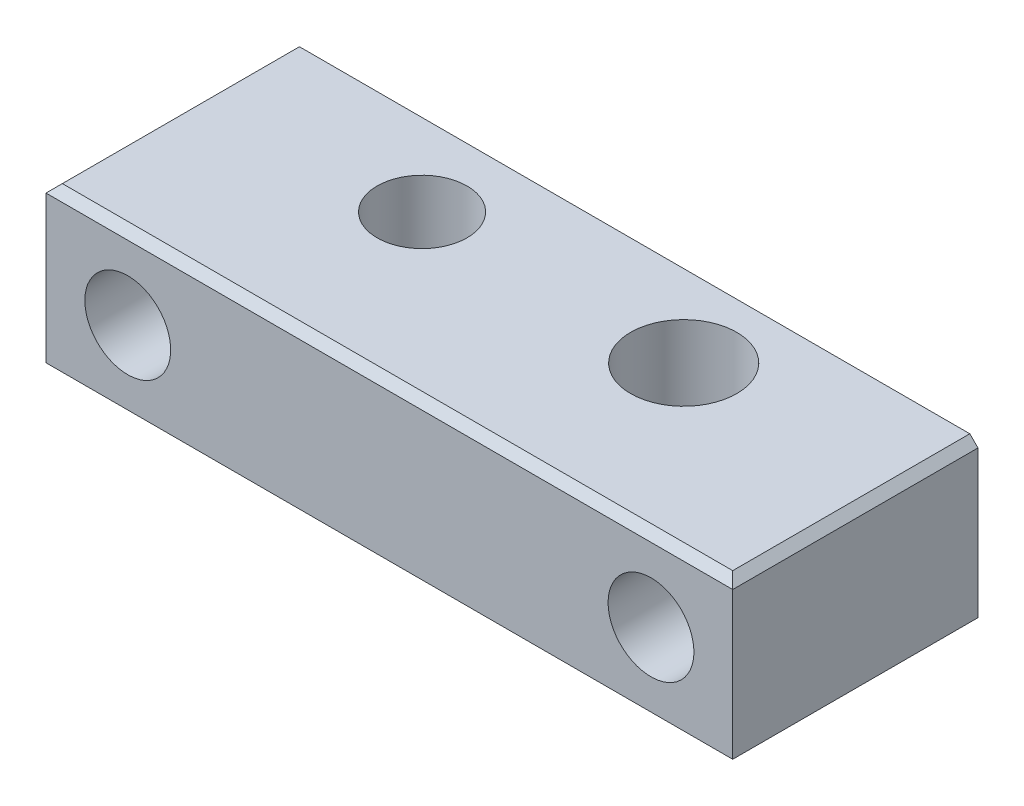
SolidWorks part; units mm, degrees
ref_plane "Front Plane" through (0, 0, 0) normal (0, 0, 1) x (1, 0, 0)
ref_plane "Top Plane" through (0, 0, 0) normal (0, 1, 0) x (1, 0, 0)
ref_plane "Right Plane" through (0, 0, 0) normal (1, 0, 0) x (0, 0, -1)
sketch "Sketch1" plane through (0, 0, 0) normal (0, 1, 0) x (1, 0, 0)
  line L1 (-66.675, -23.8125) -> (66.675, -23.8125)
  line L2 (-66.675, -23.8125) -> (-66.675, 23.8125)
  line L3 (-66.675, 23.8125) -> (66.675, 23.8125)
  line L4 (66.675, -23.8125) -> (66.675, 23.8125)
  line L5 (-66.675, -23.8125) -> (66.675, 23.8125) construction
  line L6 (-66.675, 23.8125) -> (66.675, -23.8125) construction
  point P0 (0, 0)
  dimension "D1" = 66.675
  dimension "D2" = 23.8125
extrude "Boss-Extrude1" add sketch "Sketch1" along normal mid plane 31.7246
sketch "Sketch2" plane through (0, 0, 0) normal (0, 0, 1) x (1, 0, 0)
  circle A0 centre (-50.8, -0.0127) radius 8.3312
  circle A1 centre (50.8, -0.0127) radius 8.3312
  point P4 (0, 0)
  dimension "D1" = 16.6624
  dimension "D2" = 16.6624
  dimension "D3" = 101.6
  dimension "D4" = 50.8
  dimension "D5" = 0.0127
extrude "Cut-Extrude2" cut sketch "Sketch2" along normal blind 133.35 from offset 23.8125
sketch "Sketch3" plane through (0, 0, 0) normal (0, 0, 1) x (1, 0, 0)
  circle A0 centre (-50.8, -0.0127) radius 12.7
  circle A1 centre (50.8, -0.0127) radius 12.7
  point P4 (0, 0)
  dimension "D1" = 25.4
  dimension "D2" = 25.4
  dimension "D3" = 101.6
  dimension "D4" = 50.8
  dimension "D5" = 0.0127
extrude "Cut-Extrude4" cut sketch "Sketch3" along normal blind 15.875 from offset 23.8125
sketch "Sketch4" plane through (0, 0, 0) normal (0, 1, 0) x (1, 0, 0)
  circle A0 centre (25.4, 7.9375) radius 10.3124
  point P2 (0, 0)
  dimension "D1" = 20.6248
  dimension "D2" = 25.4
  dimension "D3" = 7.9375
extrude "Cut-Extrude6" cut sketch "Sketch4" along normal through all from offset 15.8623
hole_wizard "3/4-16 Tapped Hole1" positions "Sketch6" profile "Sketch5" tap size "3/4-16" standard "ANSI Inch"
sketch "Sketch6" plane through (0, -15.8623, 0) normal (0, -1, 0) x (-1, 0, 0)
  line L0 (0, 0) -> (25.4, 7.9375) construction
  line L1 (-66.675, -23.8125) -> (-66.675, 23.8125) construction
  line L2 (66.675, -23.8125) -> (-66.675, -23.8125) construction
  point P0 (25.4, 7.9375)
  dimension "D1" = 92.075
  dimension "D2" = 31.75
sketch "Sketch5" plane through (-25.4, -15.8623, -7.9375) normal (1, 0, 0) x (0, 0, -1)
  line L0 (0, 0) -> (0, 36.9709)
  line L1 (0, 36.9709) -> (8.7312, 31.7246)
  line L2 (8.7312, 31.7246) -> (8.7312, 0)
  line L5 (8.7312, 0) -> (0, 0)
  line L10 (0, 36.9709) -> (-8.7312, 31.7246) construction
  line L11 (0, -6.35) -> (0, 107.95) construction
  dimension "Tap Drill Dia." = 17.4625
  dimension "Tap Drill Depth" = 31.7246
  dimension "Drill Angle" = 118
cosmetic thread "Hole Thread1" parameters "D1"=38.1, "D2"=19.05
chamfer "Chamfer1" distance 1.5875 angle 45 6 edges at (66.675, 15.8623, 0) (0, 15.8623, 23.8125) (-66.675, 15.8623, 0) (66.675, -15.8623, 0) (0, -15.8623, 23.8125) (-66.675, -15.8623, 0)
